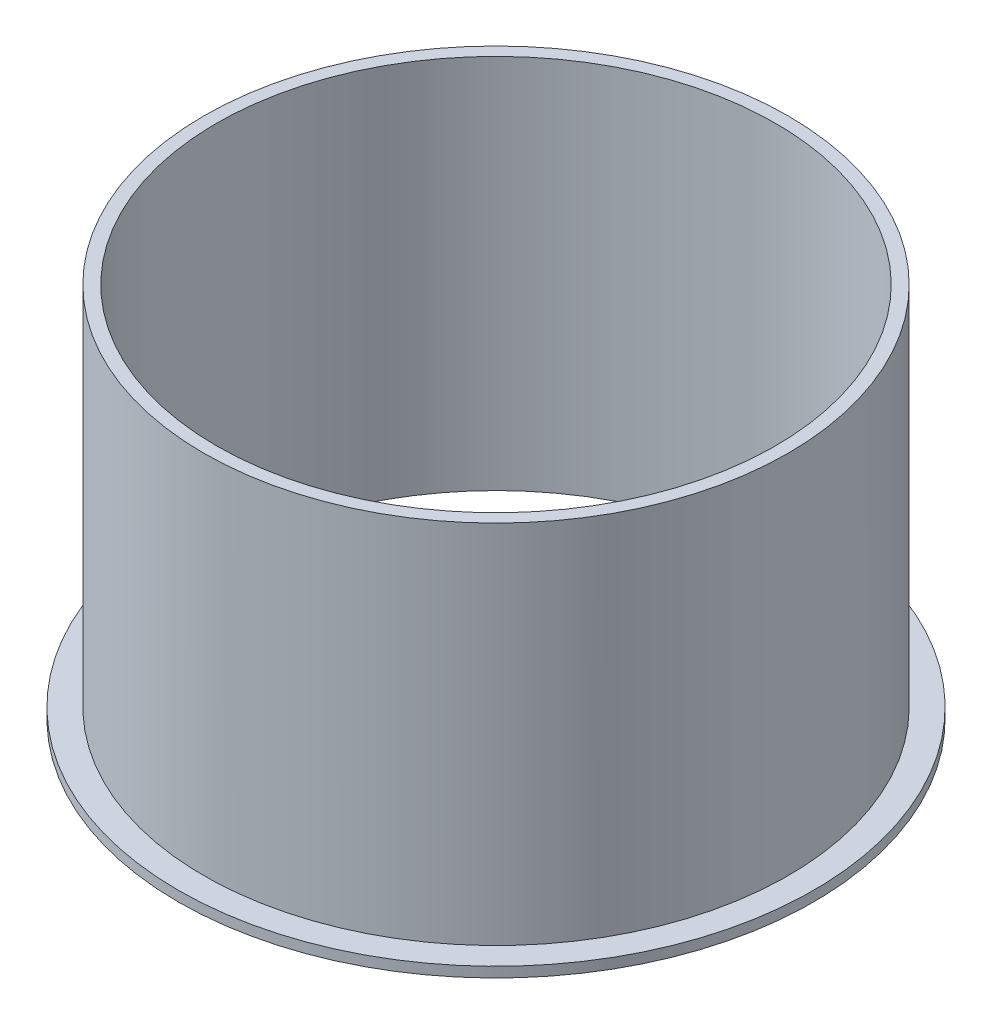
SolidWorks part; units mm, degrees
ref_plane "Front Plane" through (0, 0, 0) normal (0, 0, 1) x (1, 0, 0)
ref_plane "Top Plane" through (0, 0, 0) normal (0, 1, 0) x (1, 0, 0)
ref_plane "Right Plane" through (0, 0, 0) normal (1, 0, 0) x (0, 0, -1)
sketch "Sketch1" plane through (0, 0, 0) normal (0, 1, 0) x (1, 0, 0)
  circle A0 centre (0, 0) radius 55
  circle A1 centre (0, 0) radius 57.5
  dimension "D1" = 115
  dimension "D2" = 110
extrude "Boss-Extrude1" add sketch "Sketch1" along normal blind 74
ref_plane "Plane1" through (0, 0, 0) normal (0, -1, 0) x (-1, 0, 0)
sketch "Sketch2" plane through (0, 0, 0) normal (0, -1, 0) x (-1, 0, 0)
  circle A0 centre (0, 0) radius 62.5
  circle A1 centre (0, 0) radius 57.5
  dimension "D1" = 125
extrude "Boss-Extrude2" add sketch "Sketch2" against normal blind 2
